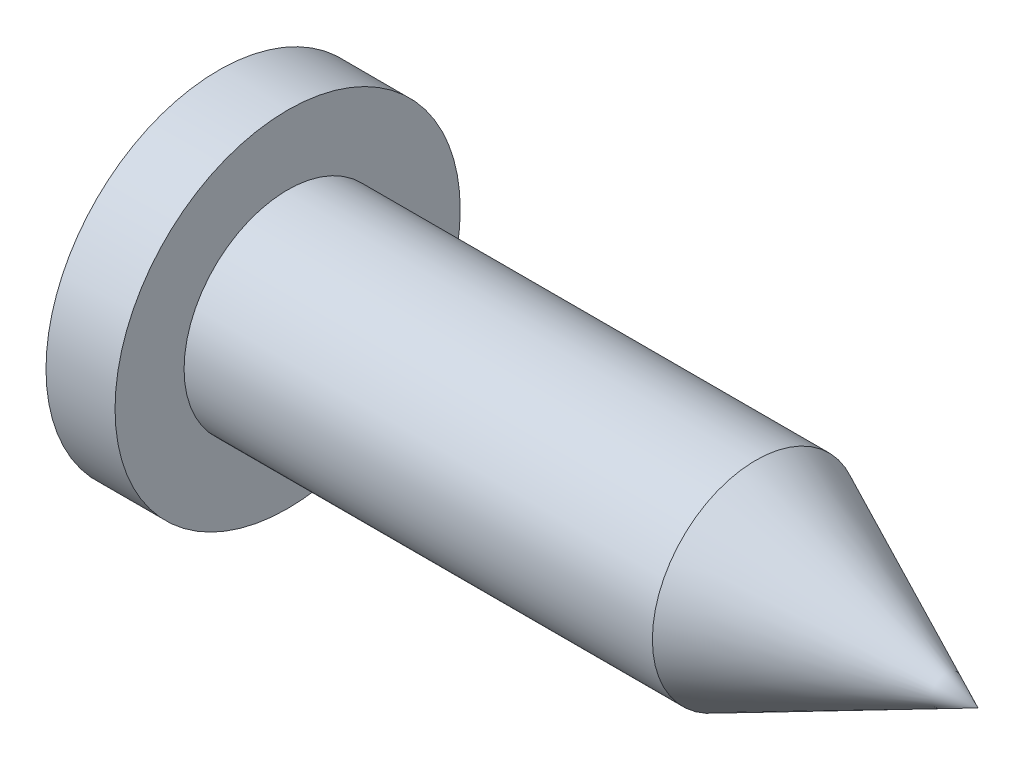
SolidWorks part; units mm, degrees
material "普通碳钢"
ref_plane "前视" through (0, 0, 0) normal (0, 0, 1) x (1, 0, 0)
ref_plane "上视" through (0, 0, 0) normal (0, 1, 0) x (1, 0, 0)
ref_plane "右视" through (0, 0, 0) normal (1, 0, 0) x (0, 0, -1)
sketch "草图1" plane through (0, 0, 0) normal (0, 0, 1) x (1, 0, 0)
  line L0 (-93.8525, 0) -> (93.8525, 0) construction
  line L1 (1.5, 2.5) -> (1.5, 1.5)
  line L2 (1.5, 1.5) -> (8.2832, 1.5)
  line L3 (8.2832, 1.5) -> (11.5, 0)
  line L4 (11.5, 0) -> (0, 0)
  line L5 (0.5, 2.5) -> (1.5, 2.5)
  arc A0 (0.5, 2.5) -> (0, 0) centre (6.5, 0) ccw
  dimension "D3" = 6.5
  dimension "D1" = 5
  dimension "D2" = 1.5
  dimension "D4" = 3
  dimension "D5" = 10
  dimension "D6" = 25
revolve "旋转1" add sketch "草图1" angle 360 about L0
sketch "草图2" plane through (0, 0, 0) normal (1, 0, 0) x (0, 0, -1)
  line L0 (0, 5.4043) -> (0, -5.4043) construction
  line L1 (1.5, 0.25) -> (1.05, 0.25)
  line L2 (1.5, 0.25) -> (1.5, -0.25)
  line L3 (1.5, -0.25) -> (1.05, -0.25)
  line L4 (-1.5, 0.25) -> (-1.5, -0.25)
  line L5 (0.25, 1.5) -> (-0.25, 1.5)
  line L6 (0.25, 1.5) -> (0.25, 1.05)
  line L7 (0.25, -1.5) -> (-0.25, -1.5)
  line L8 (-0.25, 1.5) -> (-0.25, 1.05)
  line L9 (6.2198, 0) -> (-6.2198, 0) construction
  line L10 (-0.25, -1.05) -> (-0.25, -1.5)
  line L11 (-1.05, 0.25) -> (-1.5, 0.25)
  line L12 (0.25, -1.05) -> (0.25, -1.5)
  line L13 (-1.05, -0.25) -> (-1.5, -0.25)
  arc A0 (-0.25, 1.05) -> (-1.05, 0.25) centre (-1.05, 1.05) cw
  arc A1 (1.05, 0.25) -> (0.25, 1.05) centre (1.05, 1.05) cw
  arc A2 (0.25, -1.05) -> (1.05, -0.25) centre (1.05, -1.05) cw
  arc A3 (-0.25, -1.05) -> (-1.05, -0.25) centre (-1.05, -1.05) ccw
  point P19 (-0.25, 0.25)
  point P26 (-0.25, -0.25)
  dimension "D4" = 0.8
  dimension "D1" = 3
  dimension "D2" = 3
  dimension "D3" = 0.5
extrude "切除-拉伸1" cut sketch "草图2" along normal blind 0.5
